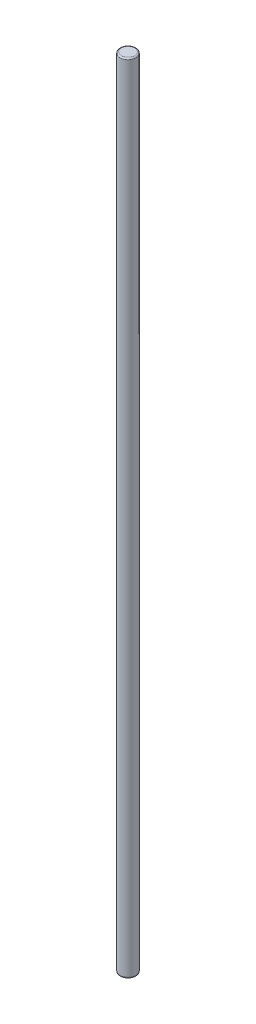
SolidWorks part; units mm, degrees
ref_plane "Front Plane" through (0, 0, 0) normal (0, 0, 1) x (1, 0, 0)
ref_plane "Top Plane" through (0, 0, 0) normal (0, 1, 0) x (1, 0, 0)
ref_plane "Right Plane" through (0, 0, 0) normal (1, 0, 0) x (0, 0, -1)
sketch "Sketch1" plane through (0, 0, 0) normal (0, 1, 0) x (1, 0, 0)
  circle A0 centre (0, 0) radius 6
  dimension "D1" = 12
extrude "Boss-Extrude1" add sketch "Sketch1" along normal blind 600
fillet "Fillet1" radius 1 2 edges at (0, 0, 6) (0, 600, 6)
